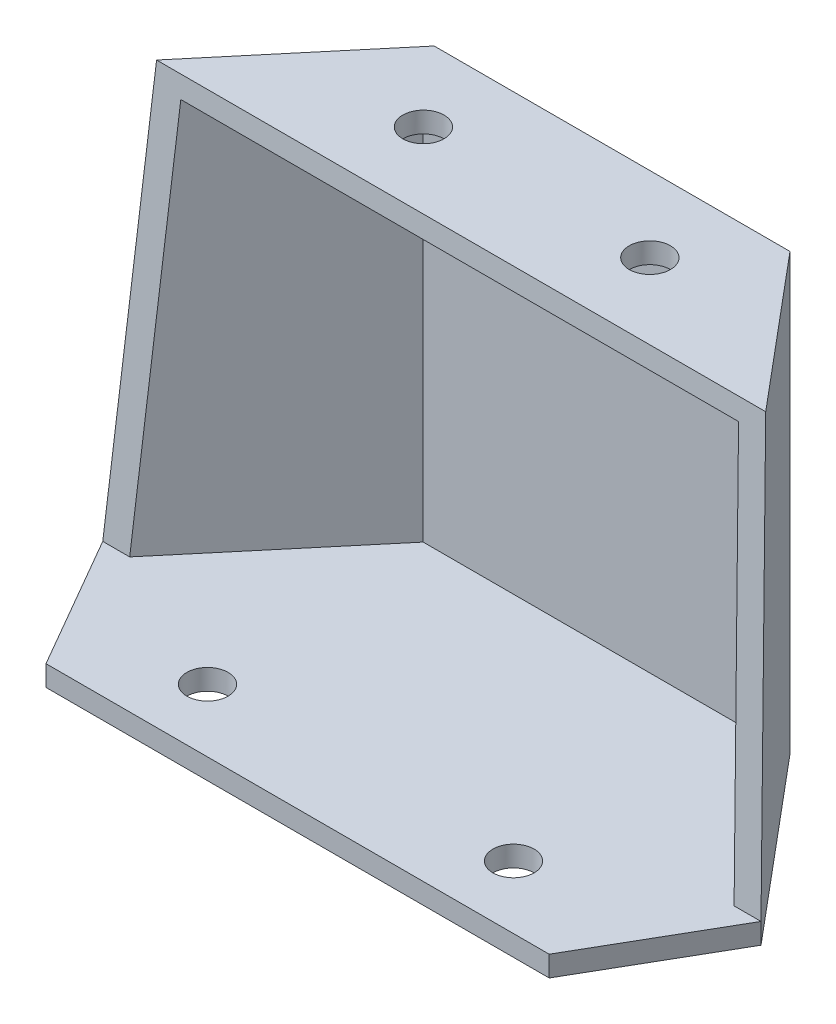
SolidWorks part; units mm, degrees
ref_plane "前视基准面" through (0, 0, 0) normal (0, 0, 1) x (1, 0, 0)
ref_plane "上视基准面" through (0, 0, 0) normal (0, 1, 0) x (1, 0, 0)
ref_plane "右视基准面" through (0, 0, 0) normal (1, 0, 0) x (0, 0, -1)
other "Configuration Table"
sketch "草图1" plane through (0, 0, 0) normal (0, 1, 0) x (1, 0, 0)
  line L0 (0, 0) -> (0, 152.5) construction
  line L1 (122, 0) -> (-122, 0)
  line L2 (-122, 0) -> (-159.5924, 65.1119)
  line L3 (-159.5924, 65.1119) -> (-86.265, 152.5)
  line L4 (-86.265, 152.5) -> (86.265, 152.5)
  line L5 (159.5924, 65.1119) -> (86.265, 152.5)
  line L6 (122, 0) -> (159.5924, 65.1119)
  dimension "D1" = 244
  dimension "D2" = 30
  dimension "D3" = 40
  dimension "D4" = 152.5
  dimension "D5" = 172.53
extrude "凸台-拉伸1" add sketch "草图1" along normal blind 211
shell "抽壳1" thickness 10
sketch "草图2" plane through (0, 0, 0) normal (1, 0, 0) x (0, 0, -1)
  line L0 (79.3, 211) -> (65.1119, 10)
  line L1 (65.1119, 211) -> (152.5, 211) construction
  line L2 (65.1119, 211) -> (65.1119, 0) construction
  line L3 (65.1119, 0) -> (152.5, 0) construction
  line L4 (79.3, 211) -> (0, 211)
  line L5 (0, 211) -> (0, 10)
  line L6 (0, 211) -> (0, 0) construction
  line L7 (0, 10) -> (65.1119, 10)
  dimension "D1" = 10
  dimension "D2" = 73.2
extrude "切除-拉伸2" cut sketch "草图2" against normal through all both and the other way through all
sketch "草图3" plane through (0, 211, 0) normal (0, 1, 0) x (1, 0, 0)
  line L0 (0, 0) -> (0, 152.5) construction
  line L1 (86.265, 152.5) -> (-86.265, 152.5) construction
  circle A0 centre (-54.9, 115.9) radius 10
  circle A1 centre (54.9, 115.9) radius 10
  dimension "D1" = 20
  dimension "D2" = 109.8
  dimension "D3" = 36.6
extrude "切除-拉伸3" cut sketch "草图3" against normal up to next
sketch "草图4" plane through (0, 10, 0) normal (0, 1, 0) x (1, 0, 0)
  line L0 (0, 0) -> (0, 79.3) construction
  line L1 (-147.6871, 79.3) -> (147.6871, 79.3) construction
  line L4 (-122, 0) -> (122, 0) construction
  circle A0 centre (-74.2, 30.5) radius 10
  circle A1 centre (74.2, 30.5) radius 10
  dimension "D1" = 20
  dimension "D2" = 30.5
extrude "切除-拉伸4" cut sketch "草图4" against normal up to next
